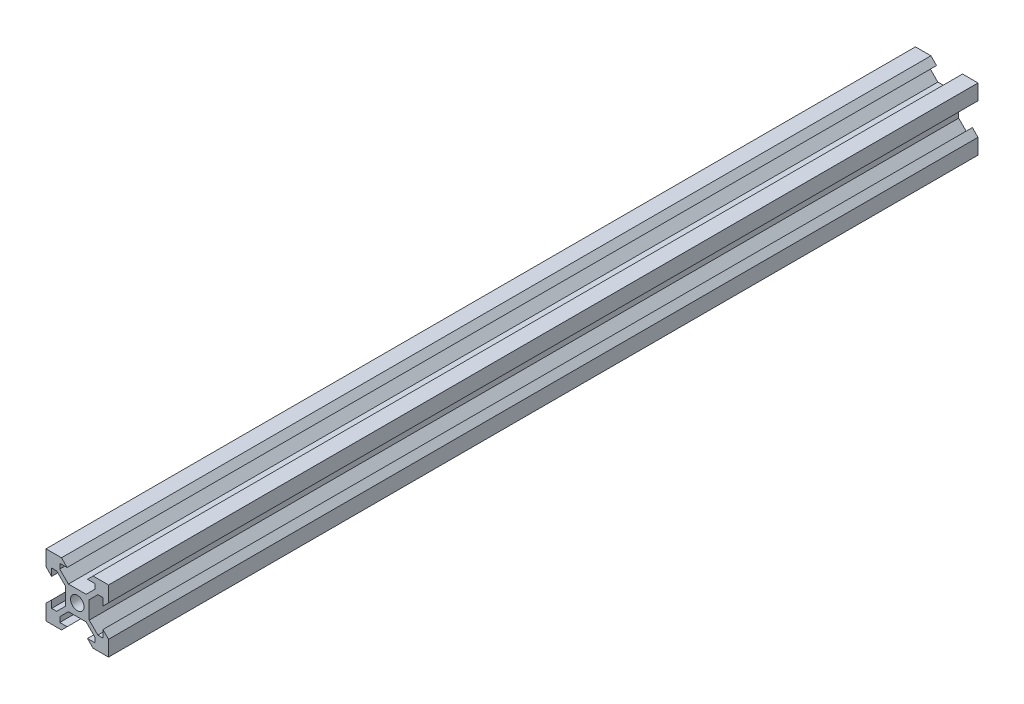
SolidWorks part; units mm, degrees
ref_plane "Alzado" through (0, 0, 0) normal (0, 0, 1) x (1, 0, 0)
ref_plane "Planta" through (0, 0, 0) normal (0, 1, 0) x (1, 0, 0)
ref_plane "Vista lateral" through (0, 0, 0) normal (1, 0, 0) x (0, 0, -1)
sketch "Croquis1" plane through (0, 0, 0) normal (0, 0, 1) x (1, 0, 0)
  line L0 (0, 0) -> (0, -20) construction
  line L2 (0, 0) -> (0, -0.5674)
  line L5 (6.175, -7.1649) -> (6.175, -12.8351)
  line L6 (7.1649, -13.825) -> (12.8351, -13.825)
  line L7 (13.825, -7.1649) -> (13.825, -12.8351)
  line L8 (7.1649, -6.175) -> (12.8351, -6.175)
  line L9 (6.175, -13.825) -> (13.825, -13.825) construction
  line L10 (13.825, -6.175) -> (13.825, -13.825) construction
  line L12 (10, -10) -> (32.1172, -10) construction
  line L13 (13.25, -18.2) -> (15.05, -20)
  line L14 (20, -20) -> (15.6, -20)
  line L15 (20, -20) -> (20, -15.6)
  line L16 (18.2, -15.6) -> (16.5899, -15.6)
  line L32 (15.6, -18.2) -> (15.6, -16.5899)
  line L33 (10, -10) -> (10, -23.2493) construction
  line L34 (4.4, -18.2) -> (4.4, -16.5899)
  line L35 (7.1649, -13.825) -> (4.4, -16.5899)
  line L36 (15.6, -18.2) -> (13.25, -18.2)
  line L38 (15.6, -20) -> (15.05, -20)
  line L40 (15.05, -20) -> (20, -20)
  line L41 (0, -20) -> (20, -20) construction
  line L42 (6.175, -12.8351) -> (3.4101, -15.6)
  line L43 (18.2, -13.25) -> (20, -15.05)
  line L44 (20, -20) -> (18.2, -20)
  line L45 (20, -20) -> (20, -15.05)
  line L48 (20, -15.05) -> (20, -20)
  line L49 (20, 0) -> (20, -20) construction
  line L50 (18.2, -15.6) -> (18.2, -13.25)
  line L51 (12.8351, -13.825) -> (15.6, -16.5899)
  line L52 (13.825, -12.8351) -> (16.5899, -15.6)
  line L53 (1.8, -15.6) -> (3.4101, -15.6)
  line L54 (1.8, -15.6) -> (1.8, -13.25)
  line L55 (1.8, -13.25) -> (0, -15.05)
  line L56 (0, 0) -> (20, 0) construction
  line L57 (0, -20) -> (0, -15.6)
  line L58 (0, -15.6) -> (0, -15.05)
  line L59 (0, -20) -> (4.4, -20)
  line L60 (0, -20) -> (4.95, -20)
  line L61 (6.75, -18.2) -> (4.95, -20)
  line L62 (4.4, -18.2) -> (6.75, -18.2)
  line L63 (1.8, -4.4) -> (3.4101, -4.4)
  line L64 (6.175, -7.1649) -> (3.4101, -4.4)
  line L65 (7.1649, -6.175) -> (4.4, -3.4101)
  line L66 (4.4, -1.8) -> (4.4, -3.4101)
  line L67 (4.4, -1.8) -> (6.75, -1.8)
  line L68 (6.75, -1.8) -> (4.95, 0)
  line L69 (0, 0) -> (4.4, 0)
  line L70 (4.4, 0) -> (4.95, 0)
  line L71 (0, 0) -> (0, -4.4)
  line L72 (0, 0) -> (0, -4.95)
  line L73 (1.8, -6.75) -> (0, -4.95)
  line L74 (1.8, -4.4) -> (1.8, -6.75)
  line L75 (15.6, -1.8) -> (15.6, -3.4101)
  line L76 (12.8351, -6.175) -> (15.6, -3.4101)
  line L77 (13.825, -7.1649) -> (16.5899, -4.4)
  line L78 (18.2, -4.4) -> (16.5899, -4.4)
  line L79 (18.2, -4.4) -> (18.2, -6.75)
  line L80 (18.2, -6.75) -> (20, -4.95)
  line L81 (20, 0) -> (20, -4.4)
  line L82 (20, -4.4) -> (20, -4.95)
  line L83 (20, 0) -> (15.6, 0)
  line L84 (20, 0) -> (15.05, 0)
  line L85 (13.25, -1.8) -> (15.05, 0)
  line L86 (15.6, -1.8) -> (13.25, -1.8)
  line L87 (6.175, -6.175) -> (13.825, -6.175) construction
  line L88 (6.175, -6.175) -> (6.175, -13.825) construction
  circle A0 centre (10, -10) radius 2.15
  point P69 (10, -10)
  dimension "D3" = 4.3
  dimension "D2" = 4
  dimension "D11" = 4.4
  dimension "D15" = 4.4
  dimension "D16" = 6.75
extrude "Saliente-Extruir2" add sketch "Croquis1" along normal blind 278 contours L86 L75 L76 L8 L65 L66 L67 L68 L70 L69 L2 L71 L72 L73 L74 L63 L64 L5 L42 L53 L54 L55 L58 L57 L59 L60 L61 L62 L34 L35 L6 L51 L32 L36 L13 L38 L40 L14 L15 L45 L43 L50 L16 L52 L7 L77 L78 L79 L80 L82 L81
